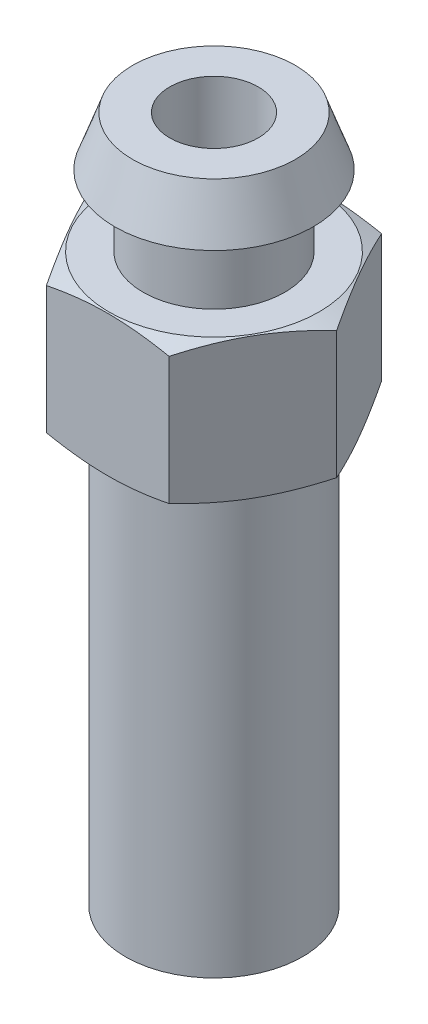
SolidWorks part; units mm, degrees
material "High-leaded brass, UNS C34200"
ref_plane "Front Plane" through (0, 0, 0) normal (0, 0, 1) x (1, 0, 0)
ref_plane "Top Plane" through (0, 0, 0) normal (0, 1, 0) x (1, 0, 0)
ref_plane "Right Plane" through (0, 0, 0) normal (1, 0, 0) x (0, 0, -1)
sketch "Sketch1" plane through (0, 0, 0) normal (0, 1, 0) x (1, 0, 0)
  line L1 (2.1997, 3.81) -> (-2.1997, 3.81)
  line L2 (-2.1997, 3.81) -> (-4.3994, 0)
  line L3 (-4.3994, 0) -> (-2.1997, -3.81)
  line L4 (-2.1997, -3.81) -> (2.1997, -3.81)
  line L5 (2.1997, -3.81) -> (4.3994, 0)
  line L6 (4.3994, 0) -> (2.1997, 3.81)
  circle A0 centre (0, 0) radius 3.81 construction
  dimension "D1" = 7.62
extrude "Boss-Extrude1" add sketch "Sketch1" along normal blind 5.08
sketch "Sketch2" plane through (0, 5.08, 0) normal (0, 1, 0) x (1, 0, 0)
  circle A0 centre (0, 0) radius 2.54
  dimension "D1" = 5.08
extrude "Boss-Extrude2" add sketch "Sketch2" along normal blind 2.54
sketch "Sketch3" plane through (0, 7.62, 0) normal (0, 1, 0) x (1, 0, 0)
  circle A0 centre (0, 0) radius 3.556
  dimension "D1" = 7.112
ref_plane "Plane1" through (0, 9.398, 0) normal (0, 1, 0) x (1, 0, 0)
sketch "Sketch4" plane through (0, 9.398, 0) normal (0, 1, 0) x (1, 0, 0)
  circle A0 centre (0, 0) radius 2.921
  dimension "D1" = 5.842
loft "Loft1" add profiles "Sketch4", "Sketch3"
sketch "Sketch6" plane through (0, 0, 0) normal (0, 0, 1) x (1, 0, 0)
  line L0 (4.3994, 4.826) -> (3.7644, 5.08)
  line L1 (4.3994, 5.08) -> (4.3994, 0) construction
  line L2 (2.1997, 5.08) -> (4.3994, 5.08) construction
  line L3 (3.7644, 5.08) -> (4.3994, 5.08)
  line L4 (4.3994, 5.08) -> (4.3994, 4.826)
  line L5 (0, 0) -> (0, 5.08) construction
  line L6 (-2.1997, 5.08) -> (2.1997, 5.08) construction
  line L7 (-4.3994, 2.54) -> (4.3994, 2.54) construction
  line L8 (-4.3994, 5.08) -> (-4.3994, 0) construction
  line L9 (4.3994, 0) -> (4.3994, 0.254)
  line L10 (3.7644, 0) -> (4.3994, 0)
  line L11 (4.3994, 0.254) -> (3.7644, 0)
  dimension "D1" = 0.635
  dimension "D2" = 0.254
revolve "Cut-Revolve1" cut sketch "Sketch6" angle 360 about L5
sketch "Sketch7" plane through (0, 0, 0) normal (0, -1, 0) x (1, 0, 0)
  circle A0 centre (0, 0) radius 3.175
  dimension "D1" = 6.35
extrude "Boss-Extrude3" add sketch "Sketch7" along normal blind 15.24
sketch "Sketch8" plane through (0, 9.398, 0) normal (0, 1, 0) x (1, 0, 0)
  circle A0 centre (0, 0) radius 1.5875
  dimension "D1" = 3.175
extrude "Cut-Extrude1" cut sketch "Sketch8" against normal through all
